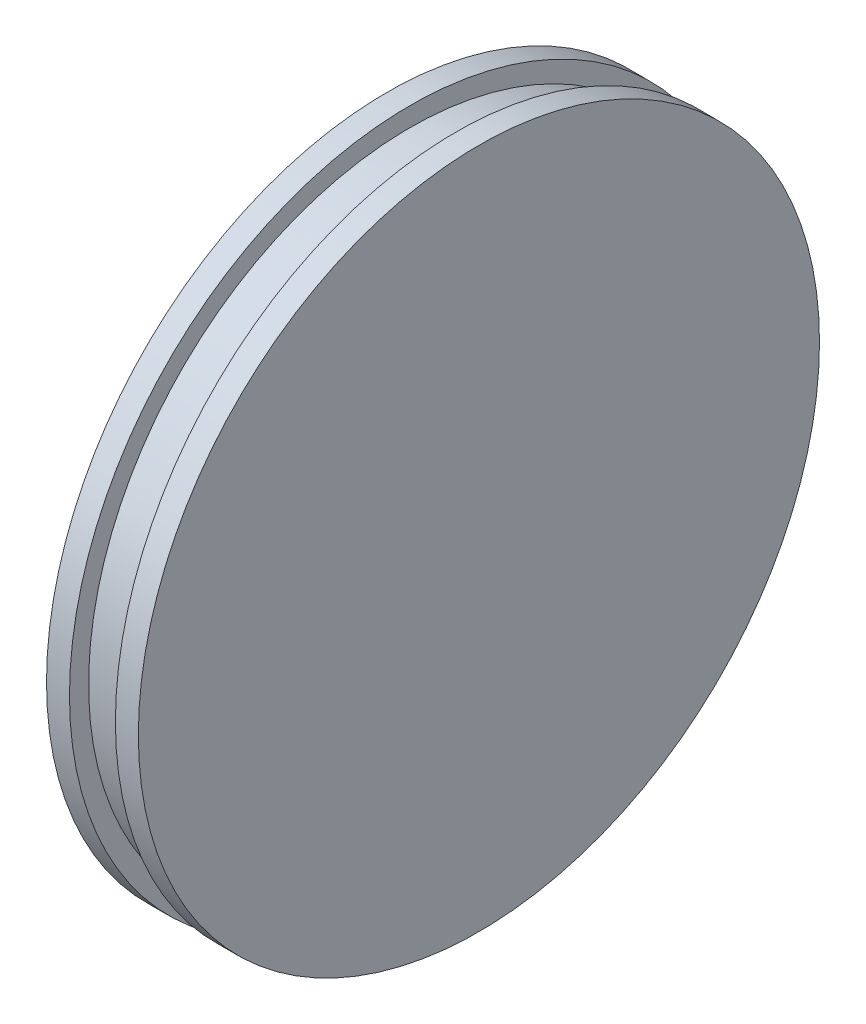
SolidWorks part; units mm, degrees
ref_plane "Front Plane" through (0, 0, 0) normal (0, 0, 1) x (1, 0, 0)
ref_plane "Top Plane" through (0, 0, 0) normal (0, 1, 0) x (1, 0, 0)
ref_plane "Right Plane" through (0, 0, 0) normal (1, 0, 0) x (0, 0, -1)
sketch "Sketch1" plane through (0, 0, 0) normal (1, 0, 0) x (0, 0, -1)
  circle A0 centre (0, 0) radius 44.5
  dimension "D1" = 89
extrude "Boss-Extrude1" add sketch "Sketch1" along normal blind 12
ref_plane "Plane1" through (3, 0, 0) normal (1, 0, 0) x (0, 0, -1)
sketch "Sketch3" plane through (3, 0, 0) normal (1, 0, 0) x (0, 0, -1)
  circle A0 centre (0, 0) radius 44.5
  circle A1 centre (0, 0) radius 42
  dimension "D1" = 84
extrude "Cut-Extrude1" cut sketch "Sketch3" along normal blind 6
sketch "Sketch4" plane through (0, 0, 0) normal (-1, 0, 0) x (0, 0, 1)
  circle A0 centre (0, 0) radius 17.5
  dimension "D1" = 35
extrude "Cut-Extrude2" cut sketch "Sketch4" against normal blind 3
